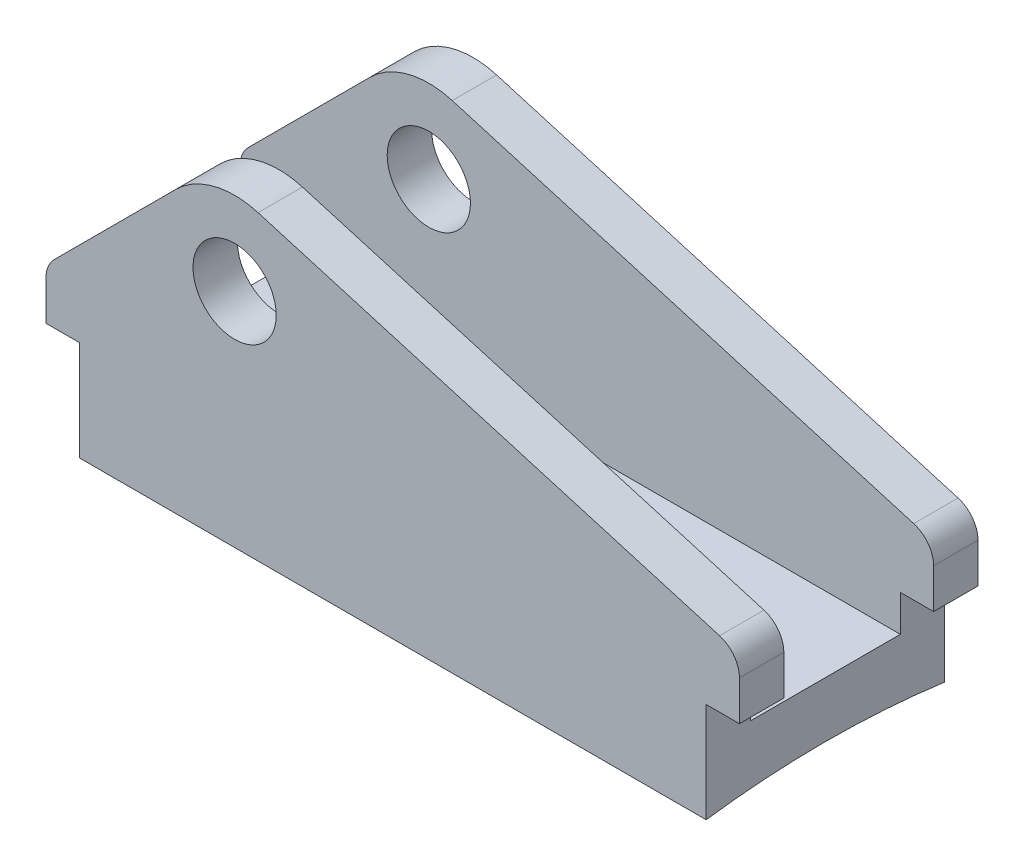
SolidWorks part; units mm, degrees
ref_plane "Front Plane" through (0, 0, 0) normal (0, 0, 1) x (1, 0, 0)
ref_plane "Top Plane" through (0, 0, 0) normal (0, 1, 0) x (1, 0, 0)
ref_plane "Right Plane" through (0, 0, 0) normal (1, 0, 0) x (0, 0, -1)
sketch "Sketch1" plane through (0, 0, 0) normal (1, 0, 0) x (0, 0, -1)
  line L0 (0, 160) -> (0, 266.8746) construction
  line L1 (-13.5, 260) -> (-13.5, 170)
  line L2 (-13.5, 170) -> (13.5, 170)
  line L3 (13.5, 170) -> (13.5, 260)
  line L4 (13.5, 260) -> (-13.5, 260)
  line L5 (-21.5, 158.5489) -> (21.5, 158.5489)
  circle A0 centre (0, 0) radius 160
  point P11 (0, 158.5489)
  point P12 (0, 0)
  point P13 (0, 0)
  point P14 (0, 0)
  dimension "D1" = 320
  dimension "D2" = 10
  dimension "D3" = 27
  dimension "D4" = 90
  dimension "D5" = 43
  dimension "D6" = 0
sketch "Sketch2" plane through (0, 0, 0) normal (0, 0, 1) x (1, 0, 0)
  line L9 (-56.5, 158.5489) -> (56.5, 158.5489)
  line L10 (56.5, 158.5489) -> (56.5, 176.5489)
  line L11 (56.5, 176.5489) -> (62.5, 176.5489)
  line L12 (62.5, 176.5489) -> (62.5, 183.691)
  line L13 (58.9102, 188.488) -> (-24.2695, 212.94)
  line L14 (-39.1066, 209.1555) -> (-61.0355, 187.2266)
  line L15 (-62.5, 183.691) -> (-62.5, 176.5489)
  line L16 (-62.5, 176.5489) -> (-56.5, 176.5489)
  line L17 (-56.5, 176.5489) -> (-56.5, 158.5489)
  line L18 (0, 167.1004) -> (0, 158.5489) construction
  line L19 (0, 160) -> (0, 266.8746) construction
  arc A2 (-24.2695, 212.94) -> (-39.1066, 209.1555) centre (-28.5, 198.5489) ccw
  arc A3 (-61.0355, 187.2266) -> (-62.5, 183.691) centre (-57.5, 183.691) ccw
  arc A4 (62.5, 183.691) -> (58.9102, 188.488) centre (57.5, 183.691) ccw
  circle A5 centre (-28.5, 198.5489) radius 7.5
  point P17 (0, 0)
  dimension "D6" = 45
  dimension "D5" = 15
  dimension "D9" = 5
  dimension "D10" = 15
  dimension "D1" = 6
  dimension "D2" = 6
  dimension "D3" = 125
  dimension "D4" = 34
  dimension "D7" = 18
  dimension "D8" = 40
extrude "Boss-Extrude1" add sketch "Sketch2" along normal mid plane 43
extrude "Cut-Extrude2" cut sketch "Sketch1" against normal mid plane 126 contours L5 A0 | L0 L2 L3 L4 | L2 L0 L4 L1 | L5 A0
